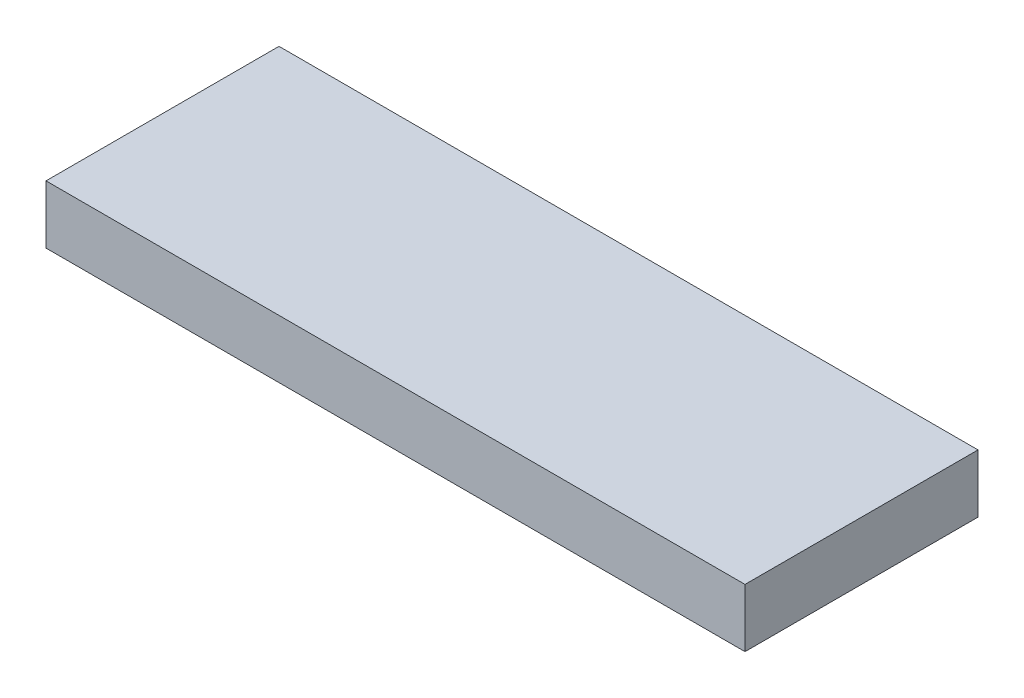
SolidWorks part; units mm, degrees
ref_plane "Front Plane" through (0, 0, 0) normal (0, 0, 1) x (1, 0, 0)
ref_plane "Top Plane" through (0, 0, 0) normal (0, 1, 0) x (1, 0, 0)
ref_plane "Right Plane" through (0, 0, 0) normal (1, 0, 0) x (0, 0, -1)
sketch "Sketch1" plane through (0, 0, 0) normal (0, 1, 0) x (1, 0, 0)
  line L1 (228.6, -76.2) -> (-228.6, -76.2)
  line L2 (228.6, -76.2) -> (228.6, 76.2)
  line L3 (228.6, 76.2) -> (-228.6, 76.2)
  line L4 (-228.6, -76.2) -> (-228.6, 76.2)
  line L5 (228.6, -76.2) -> (-228.6, 76.2) construction
  line L6 (228.6, 76.2) -> (-228.6, -76.2) construction
  point P0 (0, 0)
  dimension "D1" = 457.2
  dimension "D2" = 152.4
extrude "Boss-Extrude1" add sketch "Sketch1" along normal blind 38.1
